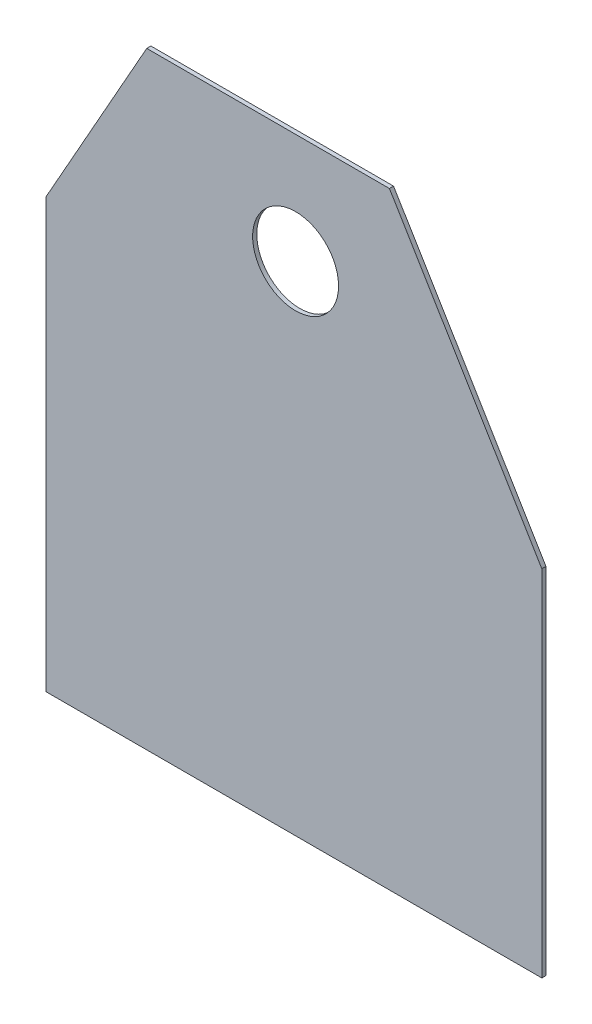
SolidWorks part; units mm, degrees
ref_plane "Спереди" through (0, 0, 0) normal (0, 0, 1) x (1, 0, 0)
ref_plane "Сверху" through (0, 0, 0) normal (0, 1, 0) x (1, 0, 0)
ref_plane "Справа" through (0, 0, 0) normal (1, 0, 0) x (0, 0, -1)
sketch "Эскиз1" plane through (0, 0, 0) normal (0, 0, 1) x (1, 0, 0)
  line L0 (64.9765, 367.7469) -> (211.882, 367.7469)
  line L1 (4, 0) -> (304.135, 0)
  line L2 (4, 0) -> (4, 259.4755)
  line L3 (64.9765, 367.7469) -> (4, 259.4755)
  line L4 (304.135, 0) -> (304.135, 214.5306)
  line L5 (211.882, 367.7469) -> (304.135, 214.5306)
  line L6 (211.882, 367.7469) -> (64.9765, 367.7469) construction
  line L7 (304.135, 214.5306) -> (211.882, 367.7469) construction
  circle A0 centre (155.0725, 301.2312) radius 26
extrude "Вытянуть1" add sketch "Эскиз1" along normal blind 2.5
